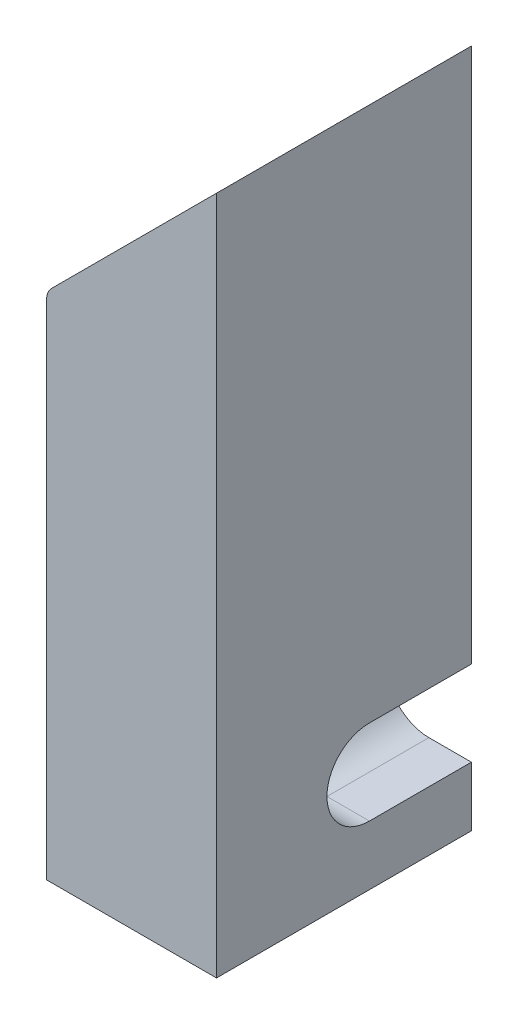
SolidWorks part; units mm, degrees
material "Acrílico (médio-alto impacto)"
ref_plane "Plano frontal" through (0, 0, 0) normal (0, 0, 1) x (1, 0, 0)
ref_plane "Plano superior" through (0, 0, 0) normal (0, 1, 0) x (1, 0, 0)
ref_plane "Plano direito" through (0, 0, 0) normal (1, 0, 0) x (0, 0, -1)
sketch "Esboço1" plane through (0, 0, 0) normal (0, 0, 1) x (1, 0, 0)
  line L0 (0, 0) -> (0, 30)
  line L1 (0, 30) -> (10, 40)
  line L2 (0, 0) -> (10, 0)
  line L3 (10, 0) -> (10, 40)
  dimension "D1" = 10
  dimension "D2" = 30
  dimension "D3" = 40
extrude "Ressalto-extrusão1" add sketch "Esboço1" along normal blind 15
sketch "Esboço2" plane through (0, 0, 0) normal (-1, 0, 0) x (0, 0, 1)
  line L0 (0, 30) -> (0, 0) construction
  line L1 (15, 0) -> (0, 0) construction
  circle A0 centre (6, 6) radius 2.5
  dimension "D1" = 5
  dimension "D2" = 6
  dimension "D3" = 6
extrude "Corte-extrusão1" cut sketch "Esboço2" against normal through all
sketch "Esboço3" plane through (0, 0, 0) normal (0, 0, -1) x (-1, 0, 0)
  line L0 (-10, 0) -> (-10, 40) construction
  line L1 (0, 0) -> (-10, 0) construction
  line L2 (-7.5, 8.5) -> (-10, 8.5)
  line L3 (-10, 8.5) -> (-10, 3.5)
  line L4 (-10, 3.5) -> (-7.5, 3.5)
  circle A0 centre (-7.5, 6) radius 2.5
  line M10 (-10, 40) -> (-10, 0)
  dimension "D1" = 5
  dimension "D2" = 2.5
  dimension "D3" = 6
  dimension "D4" = 5
  dimension "D5" = 2.5
extrude "Corte-extrusão2" cut sketch "Esboço3" against normal blind 6 contours A0 L2 M10 | A0 L3 L4 | A0
fillet "Filete1" radius 1 1 edges at (0, 30, 7.5)
